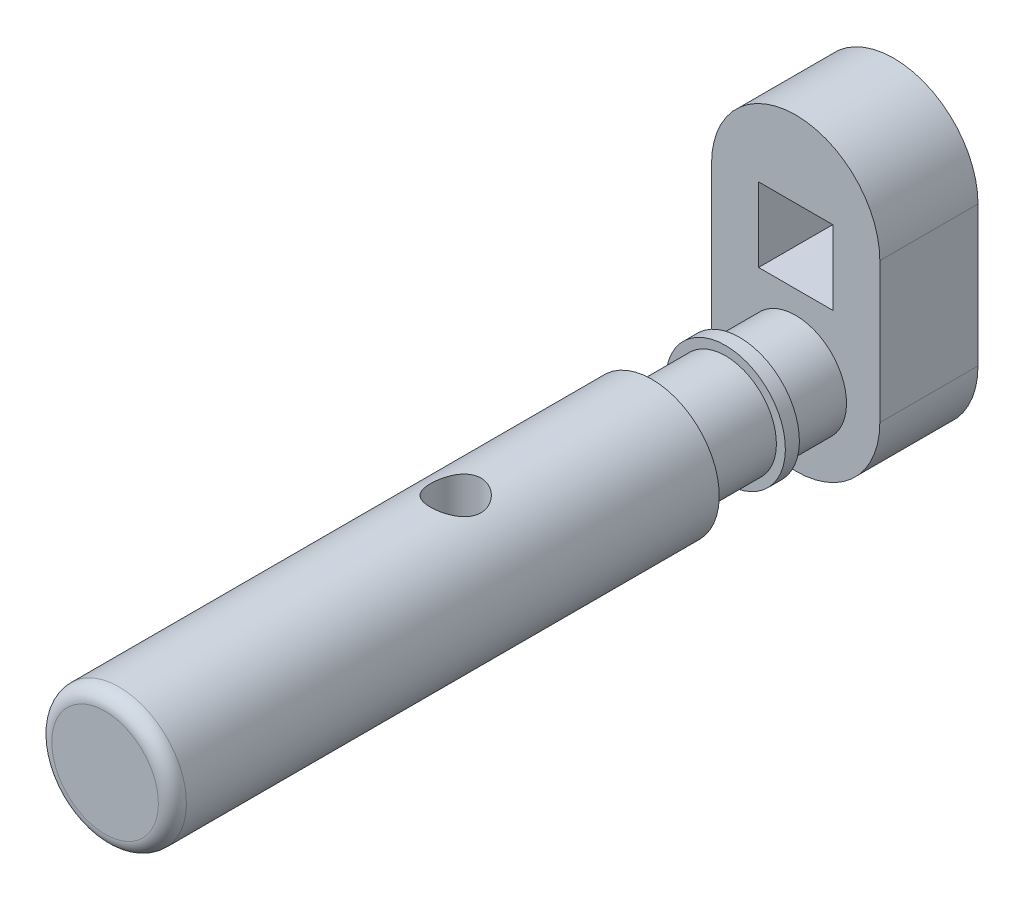
SolidWorks part; units mm, degrees
ref_plane "Front Plane" through (0, 0, 0) normal (0, 0, 1) x (1, 0, 0)
ref_plane "Top Plane" through (0, 0, 0) normal (0, 1, 0) x (1, 0, 0)
ref_plane "Right Plane" through (0, 0, 0) normal (1, 0, 0) x (0, 0, -1)
sketch "Sketch1" plane through (0, 0, 0) normal (0, 0, 1) x (1, 0, 0)
  line L0 (0, 0) -> (0, -10) construction
  line L1 (6, 0) -> (6, -10)
  line L2 (-6, 0) -> (-6, -10)
  line L4 (-2.644, -4.744) -> (2.644, -4.744)
  line L5 (-2.644, -4.744) -> (-2.644, 0.544)
  line L6 (-2.644, 0.544) -> (2.644, 0.544)
  line L7 (2.644, -4.744) -> (2.644, 0.544)
  line L8 (-2.644, -4.744) -> (2.644, 0.544) construction
  line L9 (-2.644, 0.544) -> (2.644, -4.744) construction
  arc A0 (6, 0) -> (-6, 0) centre (0, 0) ccw
  arc A1 (-6, -10) -> (6, -10) centre (0, -10) ccw
  point P3 (0, -5)
  point P8 (0, -2.1)
  dimension "D2" = 6
  dimension "D1" = 10
  dimension "D3" = 7.9
  dimension "D4" = 5.288
extrude "Boss-Extrude1" add sketch "Sketch1" along normal blind 7
sketch "Sketch3" plane through (0, 0, 7) normal (0, 0, 1) x (1, 0, 0)
  line L0 (6, -10) -> (-6, -10) construction
sketch "Sketch4" plane through (0, 0, 0) normal (1, 0, 0) x (0, 0, -1)
  line L0 (-7, -10) -> (-56.2446, -10) construction
  line L1 (-7, -13.625) -> (-11, -13.625)
  line L2 (-56.2446, -13.625) -> (-56.2446, -10)
  line L5 (-17.25, -14.2645) -> (-17.25, -13.625)
  line L6 (-12, -13.625) -> (-12, -14.2645)
  line L7 (-12, -14.2645) -> (-11, -14.2645)
  line L8 (-11, -14.2645) -> (-11, -13.625)
  line L9 (-12, -13.625) -> (-17.25, -13.625)
  line L11 (-56.2446, -10) -> (-7, -10)
  line L13 (-7, -13.625) -> (-7, -10)
  line L16 (-20.2592, -14.8) -> (-56.2446, -14.8)
  line L17 (-56.2446, -14.8) -> (-56.2446, -13.625)
  line L18 (-17.25, -14.2645) -> (-17.25, -14.8)
  line L19 (-17.25, -14.8) -> (-20.2592, -14.8)
  dimension "D2" = 5.25
  dimension "D3" = 5
  dimension "D5" = 4.8
revolve "Revolve1" add sketch "Sketch4" angle 360 about L0
fillet "Fillet1" radius 1 4 edges at (2.644, -2.1, 0) (0, -4.744, 0) (-2.644, -2.1, 0) (0, 0.544, 0)
fillet "Fillet2" radius 1 1 edges at (0, -5.2, 56.2446)
ref_point "Point2"
sketch "Sketch5" plane through (0, 0, 56.2446) normal (0, 0, 1) x (1, 0, 0)
  line L0 (0, -6.2) -> (0, -13.8) construction
  circle A0 centre (0, -10) radius 3.8 construction
ref_plane "Plane1" through (0, -5.2, 0) normal (0, 1, 0) x (1, 0, 0)
sketch "Sketch6" plane through (0, -5.2, 0) normal (0, 1, 0) x (1, 0, 0)
  line L0 (-3.8, -56.2446) -> (3.8, -56.2446) construction
  circle A0 centre (0, -31.2446) radius 1.8
  dimension "D2" = 3.6
  dimension "D1" = 25
extrude "Cut-Extrude1" cut sketch "Sketch6" against normal through all
